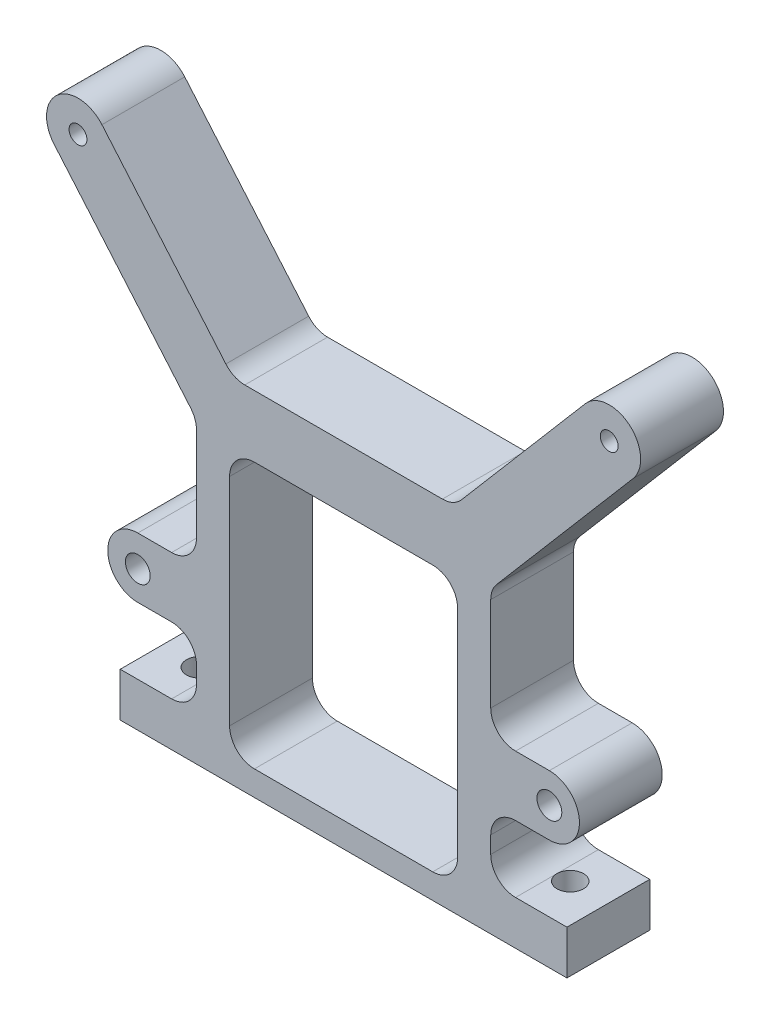
SolidWorks part; units mm, degrees
ref_plane "Front Plane" through (0, 0, 0) normal (0, 0, 1) x (1, 0, 0)
ref_plane "Top Plane" through (0, 0, 0) normal (0, 1, 0) x (1, 0, 0)
ref_plane "Right Plane" through (0, 0, 0) normal (1, 0, 0) x (0, 0, -1)
sketch "Sketch1" plane through (0, 0, 0) normal (0, 0, 1) x (1, 0, 0)
  line L0 (-44.4007, 58.9599) -> (-23.4744, 34.429)
  line L1 (-37.0594, 65.2225) -> (-18.0553, 42.9448)
  line L2 (-22.563, 17.5536) -> (-22.563, 31.9564)
  line L3 (-13.673, 32.0981) -> (13.673, 32.0981)
  line L4 (-17.483, 28.2881) -> (-17.483, -4.8321)
  line L5 (0, 105.7739) -> (0, -105.7739) construction
  line L6 (-13.673, -8.6421) -> (13.673, -8.6421)
  line L7 (-34.2514, -12.4521) -> (34.2514, -12.4521)
  line L8 (-40.7301, 62.0912) -> (-26.4461, 62.0912) construction
  line L9 (-15.1566, 41.6075) -> (15.1566, 41.6075)
  line L10 (22.563, -1.8856) -> (22.563, 0.7107)
  line L11 (34.2514, -5.6956) -> (26.373, -5.6956)
  line L12 (34.2514, -12.4521) -> (34.2514, -5.6956)
  line L13 (31.5546, 4.5207) -> (26.373, 4.5207)
  line L14 (31.5546, 13.7436) -> (26.373, 13.7436)
  line L15 (17.483, 28.2881) -> (17.483, -4.8321)
  line L16 (-31.5546, 4.5207) -> (-26.373, 4.5207)
  line L17 (-31.5546, 13.7436) -> (-26.373, 13.7436)
  line L18 (-34.2514, -12.4521) -> (-34.2514, -5.6956)
  line L19 (-34.2514, -5.6956) -> (-26.373, -5.6956)
  line L20 (-22.563, -1.8856) -> (-22.563, 0.7107)
  line L21 (22.563, 17.5536) -> (22.563, 31.9564)
  line L22 (37.0594, 65.2225) -> (18.0553, 42.9448)
  line L23 (44.4007, 58.9599) -> (23.4744, 34.429)
  circle A0 centre (-40.7301, 62.0912) radius 1.3716
  arc A1 (-37.0594, 65.2225) -> (-44.4007, 58.9599) centre (-40.7301, 62.0912) ccw
  circle A2 centre (31.5546, 9.1321) radius 1.905
  arc A3 (-22.563, 31.9564) -> (-23.4744, 34.429) centre (-26.373, 31.9564) ccw
  arc A4 (-18.0553, 42.9448) -> (-15.1566, 41.6075) centre (-15.1566, 45.4175) ccw
  circle A5 centre (40.7301, 62.0912) radius 1.3716
  arc A6 (-31.5546, 13.7436) -> (-31.5546, 4.5207) centre (-31.5546, 9.1321) ccw
  circle A7 centre (-31.5546, 8.9793) radius 1.905
  arc A8 (-22.563, 17.5536) -> (-26.373, 13.7436) centre (-26.373, 17.5536) cw
  arc A9 (-26.373, 4.5207) -> (-22.563, 0.7107) centre (-26.373, 0.7107) cw
  arc A10 (-26.373, -5.6956) -> (-22.563, -1.8856) centre (-26.373, -1.8856) ccw
  arc A11 (-13.673, 32.0981) -> (-17.483, 28.2881) centre (-13.673, 28.2881) ccw
  arc A12 (-17.483, -4.8321) -> (-13.673, -8.6421) centre (-13.673, -4.8321) ccw
  arc A13 (17.483, -4.8321) -> (13.673, -8.6421) centre (13.673, -4.8321) cw
  arc A14 (26.373, -5.6956) -> (22.563, -1.8856) centre (26.373, -1.8856) cw
  arc A15 (26.373, 4.5207) -> (22.563, 0.7107) centre (26.373, 0.7107) ccw
  arc A16 (31.5546, 13.7436) -> (31.5546, 4.5207) centre (31.5546, 9.1321) cw
  arc A17 (22.563, 17.5536) -> (26.373, 13.7436) centre (26.373, 17.5536) ccw
  arc A18 (37.0594, 65.2225) -> (44.4007, 58.9599) centre (40.7301, 62.0912) cw
  arc A19 (13.673, 32.0981) -> (17.483, 28.2881) centre (13.673, 28.2881) cw
  arc A20 (18.0553, 42.9448) -> (15.1566, 41.6075) centre (15.1566, 45.4175) cw
  arc A21 (22.563, 31.9564) -> (23.4744, 34.429) centre (26.373, 31.9564) cw
  point P11 (0, -1.0886)
  point P14 (0, 47.7615)
  point P17 (0, 32.0981)
  point P23 (0, -12.6049)
  point P24 (0, 39.5222)
  point P26 (0, -75.2646)
  point P27 (0, -12.6049)
  point P31 (0, -12.6049)
  point P32 (0, 13.5908)
  point P33 (0, 55.0155)
  point P34 (0, 68.8613)
  point P36 (0, -12.6049)
  point P37 (0, -57.9768)
  point P58 (0, -8.6421)
  point P67 (0, -12.4521)
  point P82 (0, 41.6075)
  dimension "D1" = 3.81
  dimension "D2" = 3.81
  dimension "D3" = 2.7432
extrude "Extrude1" add sketch "Sketch1" along normal blind 12.7
sketch "Sketch4" plane through (0, -12.4521, 0) normal (0, -1, 0) x (1, 0, 0)
  line L0 (-28.4072, 6.35) -> (-28.4072, 21.9705) construction
  line L1 (-28.4072, 6.35) -> (0, 6.35) construction
  line L3 (0, 0) -> (0, 26.9197) construction
  circle A0 centre (-28.4072, 6.35) radius 3.175
  circle A1 centre (28.4072, 6.35) radius 3.175
  dimension "D1" = 6.35
sketch "Sketch2" plane through (0, -12.4521, 0) normal (0, -1, 0) x (1, 0, 0)
  line L0 (0, 32.4456) -> (0, -21.6182) construction
  circle A0 centre (28.4072, 6.35) radius 2.032
  circle A1 centre (-28.4072, 6.35) radius 2.032
  dimension "D1" = 4.064
extrude "Extrude2" cut sketch "Sketch2" against normal blind 9.652
